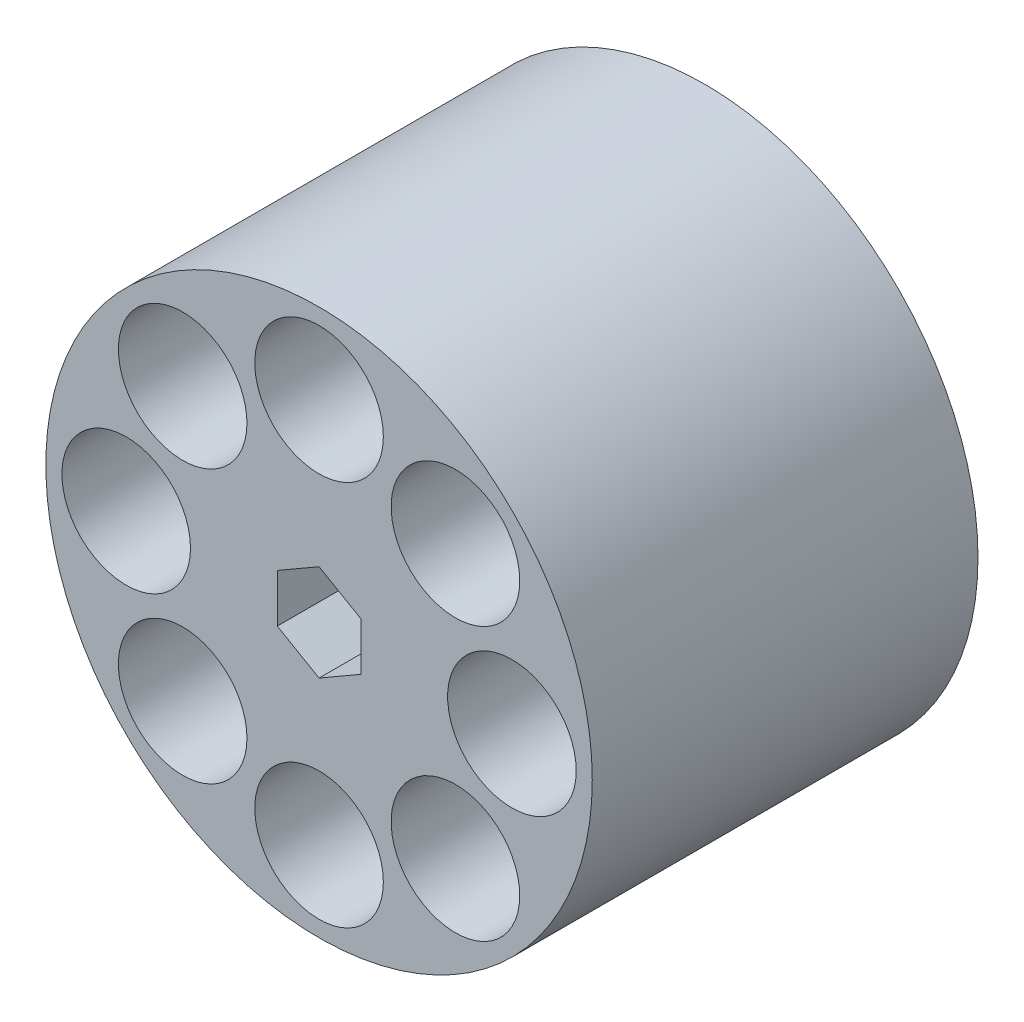
SolidWorks part; units mm, degrees
ref_plane "正面" through (0, 0, 0) normal (0, 0, 1) x (1, 0, 0)
ref_plane "平面" through (0, 0, 0) normal (0, 1, 0) x (1, 0, 0)
ref_plane "右側面" through (0, 0, 0) normal (1, 0, 0) x (0, 0, -1)
sketch "ｽｹｯﾁ1" plane through (0, 0, 0) normal (0, 0, 1) x (1, 0, 0)
  circle A0 centre (0, 0) radius 8.5
  dimension "D1" = 17
extrude "ﾎﾞｽ - 押し出し1" add sketch "ｽｹｯﾁ1" along normal blind 12
sketch "ｽｹｯﾁ2" plane through (0, 0, 12) normal (0, 0, 1) x (1, 0, 0)
  circle A0 centre (0, 0) radius 6 construction
  circle A1 centre (0, 6) radius 1
  circle A2 centre (4.2426, 4.2426) radius 1
  circle A3 centre (6, 0) radius 1
  circle A4 centre (4.2426, -4.2426) radius 1
  circle A5 centre (0, -6) radius 1
  circle A6 centre (-4.2426, -4.2426) radius 1
  circle A7 centre (-6, 0) radius 1
  circle A8 centre (-4.2426, 4.2426) radius 1
  point P21 (0, 0)
  dimension "D1" = 12
  dimension "D2" = 2
  dimension "D3" = 8
extrude "ｶｯﾄ - 押し出し1" cut sketch "ｽｹｯﾁ2" against normal blind 20
sketch "ｽｹｯﾁ3" plane through (0, 0, 12) normal (0, 0, 1) x (1, 0, 0)
  line L1 (0, 1.5) -> (-1.299, 0.75)
  line L2 (-1.299, 0.75) -> (-1.299, -0.75)
  line L3 (-1.299, -0.75) -> (0, -1.5)
  line L4 (0, -1.5) -> (1.299, -0.75)
  line L5 (1.299, -0.75) -> (1.299, 0.75)
  line L6 (1.299, 0.75) -> (0, 1.5)
  circle A0 centre (0, 0) radius 1.299 construction
  dimension "D1" = 1.5
extrude "ｶｯﾄ - 押し出し2" cut sketch "ｽｹｯﾁ3" against normal blind 8
sketch "ｽｹｯﾁ4" plane through (0, 0, 0) normal (0, 0, -1) x (-1, 0, 0)
  circle A0 centre (0, 0) radius 4.4
  dimension "D1" = 8.8
extrude "ｶｯﾄ - 押し出し3" cut sketch "ｽｹｯﾁ4" against normal blind 2
sketch "ｽｹｯﾁ5" plane through (0, 0, 12) normal (0, 0, 1) x (1, 0, 0)
  circle A0 centre (0, 6) radius 2
  circle A1 centre (4.2426, 4.2426) radius 2
  circle A2 centre (6, 0) radius 2
  circle A3 centre (4.2426, -4.2426) radius 2
  circle A4 centre (0, -6) radius 2
  circle A5 centre (-4.2426, -4.2426) radius 2
  circle A6 centre (-6, 0) radius 2
  circle A7 centre (-4.2426, 4.2426) radius 2
  point P3 (-7.4025, 4.7853)
  point P4 (0, 0)
  point P20 (0, 0)
  dimension "D1" = 4
  dimension "D2" = 8
extrude "ｶｯﾄ - 押し出し4" cut sketch "ｽｹｯﾁ5" against normal blind 4
